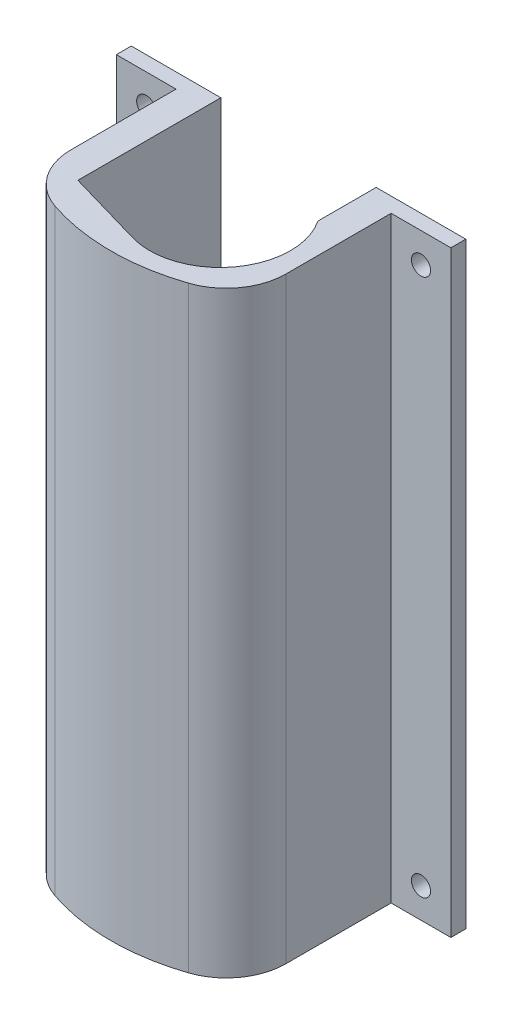
SolidWorks part; units mm, degrees
ref_plane "Front Plane" through (0, 0, 0) normal (0, 0, 1) x (1, 0, 0)
ref_plane "Top Plane" through (0, 0, 0) normal (0, 1, 0) x (1, 0, 0)
ref_plane "Right Plane" through (0, 0, 0) normal (1, 0, 0) x (0, 0, -1)
sketch "Sketch1" plane through (0, 0, 0) normal (0, 1, 0) x (1, 0, 0)
  line L0 (-20.574, -9.6521) -> (-4.162, -14.3967)
  line L1 (-4.1621, 14.3967) -> (-20.574, 9.652) construction
  line L2 (-20.574, 9.652) -> (-20.574, -9.6521)
  line L3 (-39.624, 20.7467) -> (-20.574, 20.7467)
  line L4 (-39.624, 20.7467) -> (-39.624, 17.5717)
  line L6 (12.446, 20.7467) -> (31.496, 20.7467)
  line L7 (-39.624, 17.5717) -> (-26.924, 17.5717)
  line L9 (-26.924, 17.5717) -> (-26.924, -12.8271)
  line L10 (31.496, 20.7467) -> (31.496, 17.5717)
  line L11 (31.496, 17.5717) -> (18.796, 17.5717)
  line L12 (18.796, 17.5717) -> (18.796, -12.8271)
  line L13 (-20.574, 9.652) -> (-20.574, 20.7467)
  line L14 (12.446, 20.7467) -> (12.446, 8.3478)
  arc A0 (-4.162, -14.3967) -> (12.446, 8.3478) centre (0, 0) ccw
  arc A1 (-26.924, -12.8271) -> (18.796, -12.8271) centre (-4.064, 25.294) ccw
  arc A2 (12.446, 8.3478) -> (-4.1621, 14.3967) centre (0, 0) ccw construction
  point P6 (12.446, 14.5473)
  point P16 (21.971, 20.7467)
  dimension "D2" = 14.9863
  dimension "D14" = 6.35
  dimension "D10" = 44.45
  dimension "D1" = 19.3041
  dimension "D3" = 16.4119
  dimension "D4" = 106.124
  dimension "D5" = 20.574
  dimension "D6" = 106.125
  dimension "D7" = 6.35
  dimension "D8" = 6.35
  dimension "D9" = 3.175
  dimension "D11" = 12.7
  dimension "D12" = 3.175
  dimension "D13" = 33.02
extrude "Boss-Extrude1" add sketch "Sketch1" along normal blind 127
sketch "Sketch2" plane through (0, 0, -17.5717) normal (0, 0, 1) x (1, 0, 0)
  line L0 (-39.624, 0) -> (-26.924, 0) construction
  line L1 (-39.624, 127) -> (-39.624, 0) construction
  line L2 (-39.624, 127) -> (-26.924, 127) construction
  line L3 (31.496, 127) -> (31.496, 0) construction
  circle A0 centre (-33.274, 120.65) radius 2.032
  circle A1 centre (-33.274, 6.35) radius 2.032
  circle A2 centre (25.146, 120.65) radius 2.032
  circle A3 centre (25.146, 6.35) radius 2.032
  dimension "D5" = 4.064
  dimension "D1" = 6.35
  dimension "D2" = 6.35
  dimension "D3" = 6.35
  dimension "D4" = 6.35
extrude "Cut-Extrude1" cut sketch "Sketch2" against normal through all
fillet "Fillet2" radius 12.7 2 edges at (18.796, 63.5, 12.8271) (-26.924, 63.5, 12.8271)
